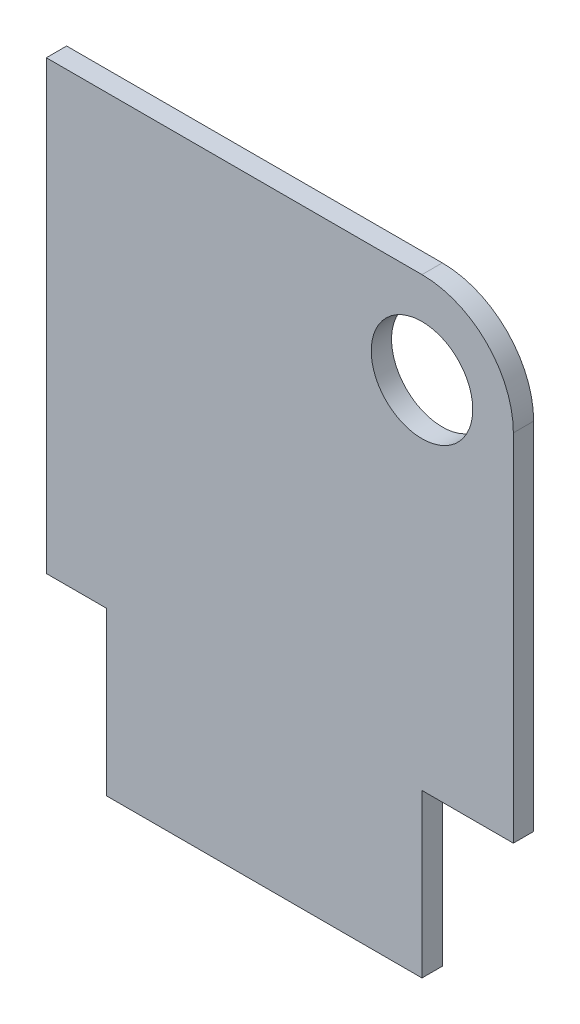
SolidWorks part; units mm, degrees
ref_plane "Front Plane" through (0, 0, 0) normal (0, 0, 1) x (1, 0, 0)
ref_plane "Top Plane" through (0, 0, 0) normal (0, 1, 0) x (1, 0, 0)
ref_plane "Right Plane" through (0, 0, 0) normal (1, 0, 0) x (0, 0, -1)
sketch "Esquisse1" plane through (0, 0, 0) normal (0, 0, 1) x (1, 0, 0)
  line L0 (-230, 80) -> (-200.3523, 80)
  line L1 (-45, 0) -> (-200.3523, 0)
  line L2 (0, 80) -> (0, 255)
  line L3 (-45, 300) -> (-230, 300)
  line L4 (-230, 80) -> (-230, 300)
  line L5 (-200.3523, 80) -> (-200.3523, 0)
  line L6 (-200.3523, 0) -> (-45, 0)
  line L7 (-45, 0) -> (-45, 80)
  line L8 (-45, 80) -> (0, 80)
  circle A0 centre (-45, 255) radius 25
  arc A1 (0, 255) -> (-45, 300) centre (-45, 255) ccw
  dimension "D3" = 45
  dimension "D4" = 45
extrude "Boss.-Extru.1" add sketch "Esquisse1" along normal blind 10 contours L2 A1 L3 L4 L0 L5 L1 L7 L8 A0
